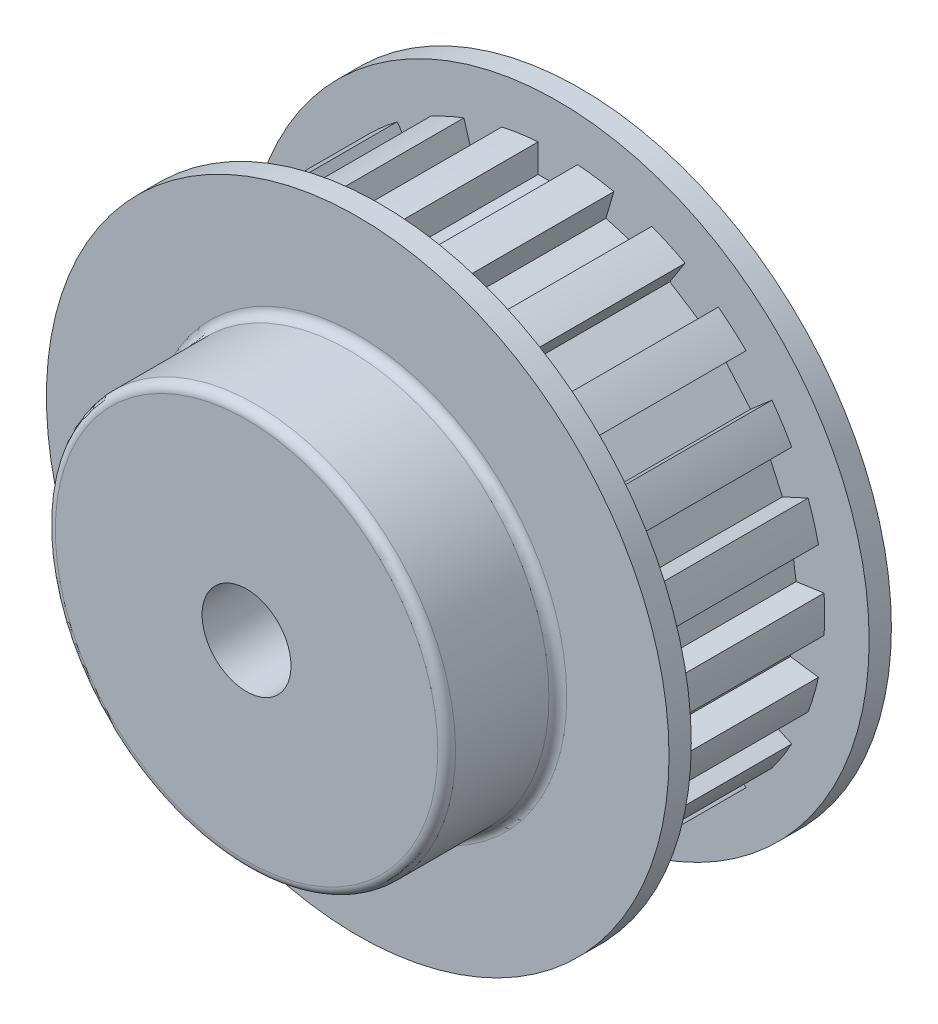
SolidWorks part; units mm, degrees
ref_plane "Front Plane" through (0, 0, 0) normal (0, 0, 1) x (1, 0, 0)
ref_plane "Top Plane" through (0, 0, 0) normal (0, 1, 0) x (1, 0, 0)
ref_plane "Right Plane" through (0, 0, 0) normal (1, 0, 0) x (0, 0, -1)
sketch "Sketch1" plane through (0, 0, 0) normal (0, 0, 1) x (1, 0, 0)
  line L0 (3.9989, 18.6255) -> (3.4311, 16.6915)
  line L2 (-1.4105, 18.9977) -> (-1.4105, 16.982)
  line L3 (-1.4105, 16.982) -> (1.4105, 16.982)
  line L4 (1.4105, 18.9977) -> (1.4105, 16.982)
  line L5 (3.4311, 16.6915) -> (6.1377, 15.8968)
  line L6 (6.7056, 17.8308) -> (6.1377, 15.8968)
  line L7 (9.0844, 16.7444) -> (7.9946, 15.0488)
  line L8 (7.9946, 15.0488) -> (10.3677, 13.5236)
  line L9 (11.4575, 15.2193) -> (10.3677, 13.5236)
  line L10 (13.4339, 13.5068) -> (11.9105, 12.1868)
  line L11 (11.9105, 12.1868) -> (13.7578, 10.0549)
  line L12 (15.2812, 11.3749) -> (13.7578, 10.0549)
  line L13 (16.695, 9.1749) -> (14.8615, 8.3376)
  line L14 (14.8615, 8.3376) -> (16.0333, 5.7716)
  line L15 (17.8669, 6.6089) -> (16.0333, 5.7716)
  line L16 (18.6036, 4.0998) -> (16.6085, 3.8129)
  line L17 (16.6085, 3.8129) -> (17.0099, 1.0207)
  line L18 (19.0051, 1.3075) -> (17.0099, 1.0207)
  line L19 (19.0051, -1.3075) -> (17.0099, -1.0207)
  line L20 (17.0099, -1.0207) -> (16.6085, -3.8129)
  line L21 (18.6036, -4.0998) -> (16.6085, -3.8129)
  line L22 (17.8669, -6.6089) -> (16.0333, -5.7716)
  line L23 (16.0333, -5.7716) -> (14.8615, -8.3376)
  line L24 (16.695, -9.1749) -> (14.8615, -8.3376)
  line L25 (15.2812, -11.3749) -> (13.7578, -10.0549)
  line L26 (13.7578, -10.0549) -> (11.9105, -12.1868)
  line L27 (13.4339, -13.5068) -> (11.9105, -12.1868)
  line L28 (11.4575, -15.2193) -> (10.3677, -13.5236)
  line L29 (10.3677, -13.5236) -> (7.9946, -15.0488)
  line L30 (9.0844, -16.7444) -> (7.9946, -15.0488)
  line L31 (6.7056, -17.8308) -> (6.1377, -15.8968)
  line L32 (6.1377, -15.8968) -> (3.4311, -16.6915)
  line L33 (3.9989, -18.6255) -> (3.4311, -16.6915)
  line L34 (1.4105, -18.9977) -> (1.4105, -16.982)
  line L35 (1.4105, -16.982) -> (-1.4105, -16.982)
  line L36 (-1.4105, -18.9977) -> (-1.4105, -16.982)
  line L37 (-3.9989, -18.6255) -> (-3.4311, -16.6915)
  line L38 (-3.4311, -16.6915) -> (-6.1377, -15.8968)
  line L39 (-6.7056, -17.8308) -> (-6.1377, -15.8968)
  line L40 (-9.0844, -16.7444) -> (-7.9946, -15.0488)
  line L41 (-7.9946, -15.0488) -> (-10.3677, -13.5236)
  line L42 (-11.4575, -15.2193) -> (-10.3677, -13.5236)
  line L43 (-13.4339, -13.5068) -> (-11.9105, -12.1868)
  line L44 (-11.9105, -12.1868) -> (-13.7578, -10.0549)
  line L45 (-15.2812, -11.3749) -> (-13.7578, -10.0549)
  line L46 (-16.695, -9.1749) -> (-14.8615, -8.3376)
  line L47 (-14.8615, -8.3376) -> (-16.0333, -5.7716)
  line L48 (-17.8669, -6.6089) -> (-16.0333, -5.7716)
  line L49 (-18.6036, -4.0998) -> (-16.6085, -3.8129)
  line L50 (-16.6085, -3.8129) -> (-17.0099, -1.0207)
  line L51 (-19.0051, -1.3075) -> (-17.0099, -1.0207)
  line L52 (-19.0051, 1.3075) -> (-17.0099, 1.0207)
  line L53 (-17.0099, 1.0207) -> (-16.6085, 3.8129)
  line L54 (-18.6036, 4.0998) -> (-16.6085, 3.8129)
  line L55 (-17.8669, 6.6089) -> (-16.0333, 5.7716)
  line L56 (-16.0333, 5.7716) -> (-14.8615, 8.3376)
  line L57 (-16.695, 9.1749) -> (-14.8615, 8.3376)
  line L58 (-15.2812, 11.3749) -> (-13.7578, 10.0549)
  line L59 (-13.7578, 10.0549) -> (-11.9105, 12.1868)
  line L60 (-13.4339, 13.5068) -> (-11.9105, 12.1868)
  line L61 (-11.4575, 15.2193) -> (-10.3677, 13.5236)
  line L62 (-10.3677, 13.5236) -> (-7.9946, 15.0488)
  line L63 (-9.0844, 16.7444) -> (-7.9946, 15.0488)
  line L64 (-6.7056, 17.8308) -> (-6.1377, 15.8968)
  line L65 (-6.1377, 15.8968) -> (-3.4311, 16.6915)
  line L66 (-3.9989, 18.6255) -> (-3.4311, 16.6915)
  arc A0 (-1.4105, 18.9977) -> (-3.9989, 18.6255) centre (0, 0) ccw
  arc A1 (-6.7056, 17.8308) -> (-9.0844, 16.7444) centre (0, 0) ccw
  arc A2 (-11.4575, 15.2193) -> (-13.4339, 13.5068) centre (0, 0) ccw
  arc A3 (-15.2812, 11.3749) -> (-16.695, 9.1749) centre (0, 0) ccw
  arc A4 (-17.8669, 6.6089) -> (-18.6036, 4.0998) centre (0, 0) ccw
  arc A5 (-19.0051, 1.3075) -> (-19.0051, -1.3075) centre (0, 0) ccw
  arc A6 (-18.6036, -4.0998) -> (-17.8669, -6.6089) centre (0, 0) ccw
  arc A7 (-16.695, -9.1749) -> (-15.2812, -11.3749) centre (0, 0) ccw
  arc A8 (-13.4339, -13.5068) -> (-11.4575, -15.2193) centre (0, 0) ccw
  arc A9 (-9.0844, -16.7444) -> (-6.7056, -17.8308) centre (0, 0) ccw
  arc A10 (-3.9989, -18.6255) -> (-1.4105, -18.9977) centre (0, 0) ccw
  arc A11 (1.4105, -18.9977) -> (3.9989, -18.6255) centre (0, 0) ccw
  arc A12 (6.7056, -17.8308) -> (9.0844, -16.7444) centre (0, 0) ccw
  arc A13 (11.4575, -15.2193) -> (13.4339, -13.5068) centre (0, 0) ccw
  arc A14 (15.2812, -11.3749) -> (16.695, -9.1749) centre (0, 0) ccw
  arc A15 (17.8669, -6.6089) -> (18.6036, -4.0998) centre (0, 0) ccw
  arc A16 (18.6036, 4.0998) -> (17.8669, 6.6089) centre (0, 0) ccw
  arc A17 (19.0051, -1.3075) -> (19.0051, 1.3075) centre (0, 0) ccw
  arc A18 (16.695, 9.1749) -> (15.2812, 11.3749) centre (0, 0) ccw
  arc A19 (13.4339, 13.5068) -> (11.4575, 15.2193) centre (0, 0) ccw
  arc A20 (9.0844, 16.7444) -> (6.7056, 17.8308) centre (0, 0) ccw
  arc A21 (3.9989, 18.6255) -> (1.4105, 18.9977) centre (0, 0) ccw
  circle A22 centre (0, 0) radius 3.175
  point P3 (0, 19.05)
  dimension "D1" = 38.1
  dimension "D3" = 6.35
  dimension "D2" = 22
extrude "Boss-Extrude3" add sketch "Sketch1" along normal blind 6.35
sketch "Sketch2" plane through (0, 0, 6.35) normal (0, 0, 1) x (1, 0, 0)
  circle A0 centre (0, 0) radius 22.225
  circle A1 centre (0, 0) radius 3.175
  dimension "D1" = 44.45
extrude "Boss-Extrude4" add sketch "Sketch2" along normal blind 1.5875
sketch "Sketch3" plane through (0, 0, 7.9375) normal (0, 0, 1) x (1, 0, 0)
  circle A0 centre (0, 0) radius 14.2875
  circle A1 centre (0, 0) radius 3.175
  dimension "D1" = 28.575
extrude "Boss-Extrude5" add sketch "Sketch3" along normal blind 7.9375
fillet "Fillet1" radius 0.635 2 edges at (14.2875, 0, 15.875) (14.2875, 0, 7.9375)
mirror "Mirror1" about plane through (0, 0, 0) normal (0, 0, 1) of "Boss-Extrude4", "Boss-Extrude3"
